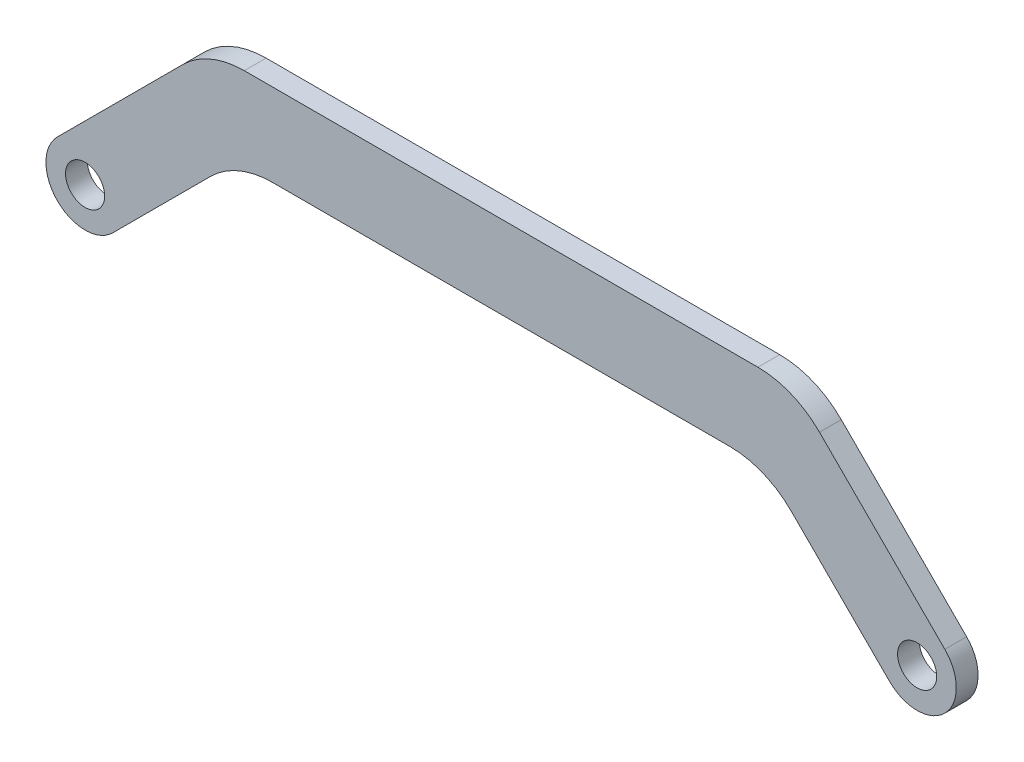
SolidWorks part; units mm, degrees
ref_plane "Front Plane" through (0, 0, 0) normal (0, 0, 1) x (1, 0, 0)
ref_plane "Top Plane" through (0, 0, 0) normal (0, 1, 0) x (1, 0, 0)
ref_plane "Right Plane" through (0, 0, 0) normal (1, 0, 0) x (0, 0, -1)
sketch "Sketch1" plane through (0, 0, 0) normal (0, 0, 1) x (1, 0, 0)
  line L0 (-6.3569, 6.3569) -> (28.2662, 40.98)
  line L1 (28.2662, 40.98) -> (162.7338, 40.98)
  line L2 (6.3569, -6.3569) -> (34.7138, 22)
  line L3 (0, 0) -> (191, 0) construction
  line L4 (95.5, 0) -> (95.5, 82.126) construction
  line L5 (34.7138, 22) -> (156.2862, 22)
  line L6 (184.6431, -6.3569) -> (156.2862, 22)
  line L7 (197.3569, 6.3569) -> (162.7338, 40.98)
  circle A0 centre (0, 0) radius 4.49
  circle A1 centre (191, 0) radius 4.49
  arc A2 (-6.3569, 6.3569) -> (6.3569, -6.3569) centre (0, 0) ccw
  arc A3 (184.6431, -6.3569) -> (197.3569, 6.3569) centre (191, 0) ccw
  point P19 (95.5, 22)
  point P22 (95.5, 40.98)
  dimension "D1" = 8.98
  dimension "D2" = 8.98
  dimension "D4" = 4.5
  dimension "D5" = 135
  dimension "D3" = 191
  dimension "D6" = 18.98
  dimension "D7" = 22
extrude "Boss-Extrude1" add sketch "Sketch1" along normal blind 5
fillet "Fillet1" radius 20 1 edges at (28.2662, 40.98, 2.5)
fillet "Fillet2" radius 20 1 edges at (34.7138, 22, 2.5)
fillet "Fillet3" radius 20 1 edges at (162.7338, 40.98, 2.5)
fillet "Fillet4" radius 20 1 edges at (156.2862, 22, 2.5)
